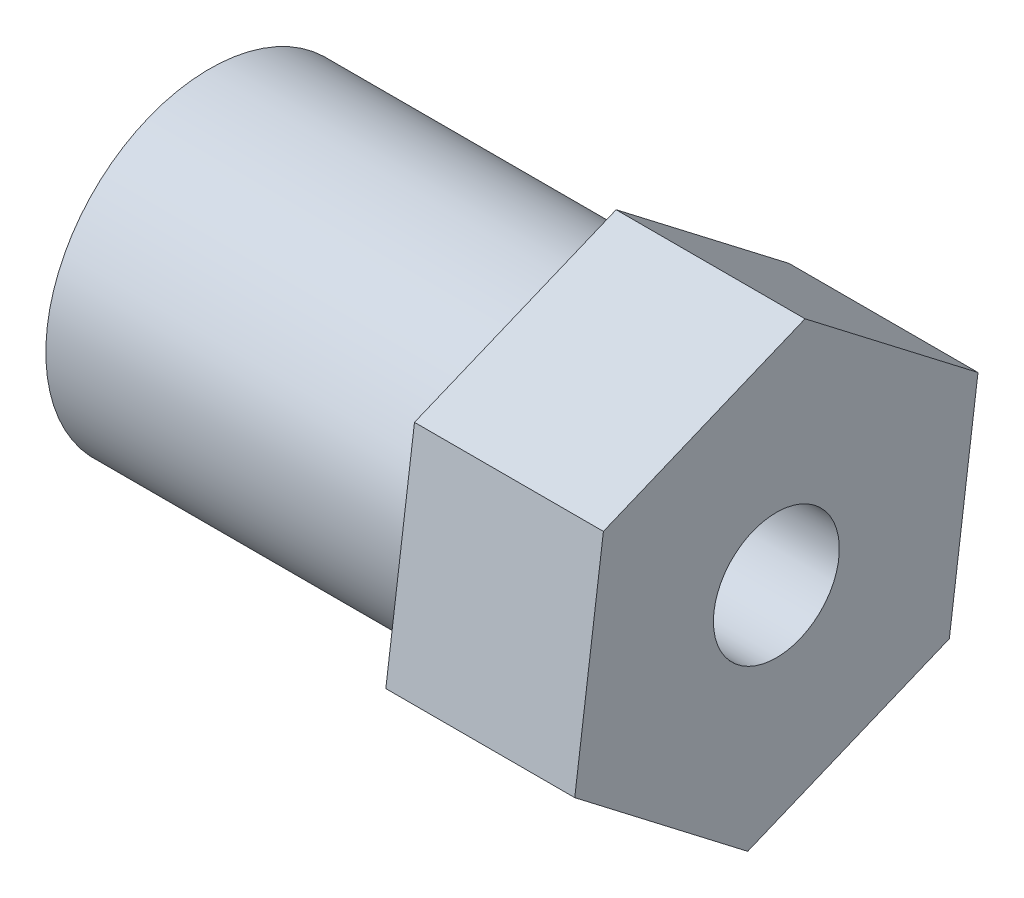
SolidWorks part; units mm, degrees
ref_plane "前视基准面" through (0, 0, 0) normal (0, 0, 1) x (1, 0, 0)
ref_plane "上视基准面" through (0, 0, 0) normal (0, 1, 0) x (1, 0, 0)
ref_plane "右视基准面" through (0, 0, 0) normal (1, 0, 0) x (0, 0, -1)
ref_plane "基准面4" through (88, 0, 0) normal (1, 0, 0) x (0, 0, -1)
sketch "草图1" plane through (88, 0, 0) normal (1, 0, 0) x (0, 0, -1)
  line L0 (27.0968, 197.3545) -> (32.5895, 193.1319)
  line L1 (32.5895, 193.1319) -> (38.9927, 195.7774)
  line L2 (38.9927, 195.7774) -> (39.9032, 202.6455)
  line L3 (39.9032, 202.6455) -> (34.4105, 206.8681)
  line L4 (34.4105, 206.8681) -> (28.0073, 204.2226)
  line L5 (28.0073, 204.2226) -> (27.0968, 197.3545)
extrude "凸台-拉伸1" add sketch "草图1" against normal blind 6
ref_plane "基准面5" through (0, 0, -33.5) normal (0, 0, 1) x (1, 0, 0)
sketch "草图2" plane through (0, 0, -33.5) normal (0, 0, 1) x (1, 0, 0)
  line L0 (70, 205.2) -> (70, 200)
  line L1 (70, 200) -> (82, 200)
  line L2 (82, 200) -> (82, 205.2)
  line L3 (82, 205.2) -> (70, 205.2)
  line L4 (70, 200) -> (82, 200) construction
revolve "旋转1" add sketch "草图2" angle 360 about L4
hole_wizard "M3.5 六角头机械螺钉的柱形沉头孔1" positions "草图4" profile "草图3" counterbore size "M3.5" standard "ANSI Metric"
sketch "草图4" plane through (70, 0, 0) normal (-1, 0, 0) x (0, 0, 1)
  point P0 (-33.5, 200)
sketch "草图3" plane through (70, 200, -33.5) normal (0, 1, 0) x (0, 0, 1)
  line L0 (0, 0) -> (0, 18)
  line L1 (0, 18) -> (2, 18)
  line L3 (2, 18) -> (2, 12)
  line L4 (2, 12) -> (2.5, 12)
  line L5 (2.5, 12) -> (2.5, 0)
  line L7 (2.5, 0) -> (0, 0)
  line L11 (0, -6.35) -> (0, 107.95) construction
  dimension "通孔孔直径" = 4
  dimension "通孔孔深度" = 18
  dimension "柱形沉头孔直径" = 5
  dimension "柱形沉头孔深度" = 12
ref_plane "基准面6" through (0, 157.2802, 64.9813) normal (0, 0.9242, 0.3818) x (1, 0, 0)
hole_wizard "Ø3.0 (3) 直径孔1" positions "草图6" profile "草图5" hole size "Ø3.0" standard "ANSI Metric"
sketch "草图6" plane through (0, 157.2802, 64.9813) normal (0, 0.9242, 0.3818) x (1, 0, 0)
  point P0 (74, 107.4819)
sketch "草图5" plane through (74, 198.3221, -34.3561) normal (1, 0, 0) x (0, -0.3818, 0.9242)
  line L0 (0, 0) -> (0, 6.9151)
  line L1 (0, 6.9151) -> (1.5, 6.9151)
  line L2 (1.5, 6.9151) -> (1.5, 0)
  line L5 (1.5, 0) -> (0, 0)
  line L11 (0, -6.35) -> (0, 107.95) construction
  dimension "通孔孔直径" = 3
  dimension "通孔孔深度" = 6.9151
